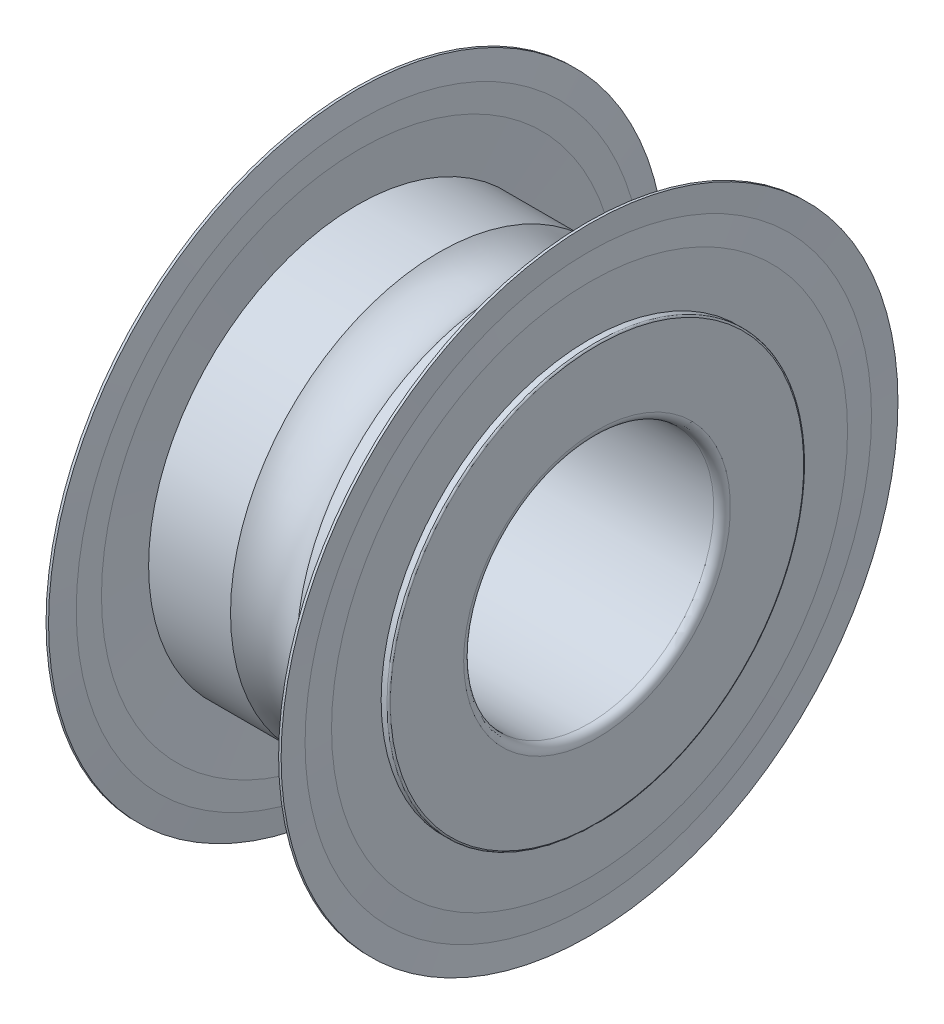
SolidWorks part; units mm, degrees
ref_plane "Front Plane" through (0, 0, 0) normal (0, 0, 1) x (1, 0, 0)
ref_plane "Top Plane" through (0, 0, 0) normal (0, 1, 0) x (1, 0, 0)
ref_plane "Right Plane" through (0, 0, 0) normal (1, 0, 0) x (0, 0, -1)
ref_plane "Plane1" through (0, 0, 0) normal (0, 0, 1) x (1, 0, 0)
sketch "Sketch1" plane through (0, 0, 0) normal (0, 0, 1) x (1, 0, 0)
  line L0 (0, 2.48) -> (0, 1.6)
  line L1 (0.1, 1.5) -> (2.9, 1.5)
  line L2 (3, 1.6) -> (3, 2.48)
  line L3 (2.98, 2.5) -> (1.8969, 2.5)
  line L4 (1.1031, 2.5) -> (0.02, 2.5)
  line L5 (50, 0) -> (-50, 0) construction
  arc A0 (0, 1.6) -> (0.1, 1.5) centre (0.1, 1.6) ccw
  arc A1 (2.9, 1.5) -> (3, 1.6) centre (2.9, 1.6) ccw
  arc A2 (3, 2.48) -> (2.98, 2.5) centre (2.98, 2.48) ccw
  arc A3 (1.8969, 2.5) -> (1.1031, 2.5) centre (1.5, 2.95) cw
  arc A4 (0.02, 2.5) -> (0, 2.48) centre (0.02, 2.48) ccw
revolve "Revolve1" add sketch "Sketch1" angle 360 about L5
ref_plane "Plane2" through (0, 0, 0) normal (0, 0, 1) x (1, 0, 0)
sketch "Sketch2" plane through (0, 0, 0) normal (0, 0, 1) x (1, 0, 0)
  line L0 (0.09, 3.7) -> (0.105, 3.3975)
  line L1 (0.105, 3.3975) -> (0.09, 3.095)
  line L2 (0.09, 3.095) -> (0.09, 2.49)
  line L3 (0.09, 2.49) -> (0.12, 2.49)
  line L4 (0.12, 2.49) -> (0.15, 3.095)
  line L5 (0.15, 3.095) -> (0.15, 3.3975)
  line L6 (0.15, 3.3975) -> (0.12, 3.7)
  line L7 (0.12, 3.7) -> (0.09, 3.7)
  line L8 (50, 0) -> (-50, 0) construction
revolve "Revolve2" add sketch "Sketch2" angle 360 about L8
ref_plane "Plane3" through (0, 0, 0) normal (0, 0, 1) x (1, 0, 0)
sketch "Sketch3" plane through (0, 0, 0) normal (0, 0, 1) x (1, 0, 0)
  line L0 (2.85, 3.3975) -> (2.85, 3.095)
  line L1 (2.85, 3.095) -> (2.88, 2.49)
  line L2 (2.88, 2.49) -> (2.91, 2.49)
  line L3 (2.91, 2.49) -> (2.91, 3.095)
  line L4 (2.91, 3.095) -> (2.895, 3.3975)
  line L5 (2.895, 3.3975) -> (2.91, 3.7)
  line L6 (2.91, 3.7) -> (2.88, 3.7)
  line L7 (2.88, 3.7) -> (2.85, 3.3975)
  line L8 (50, 0) -> (-50, 0) construction
revolve "Revolve3" add sketch "Sketch3" angle 360 about L8
